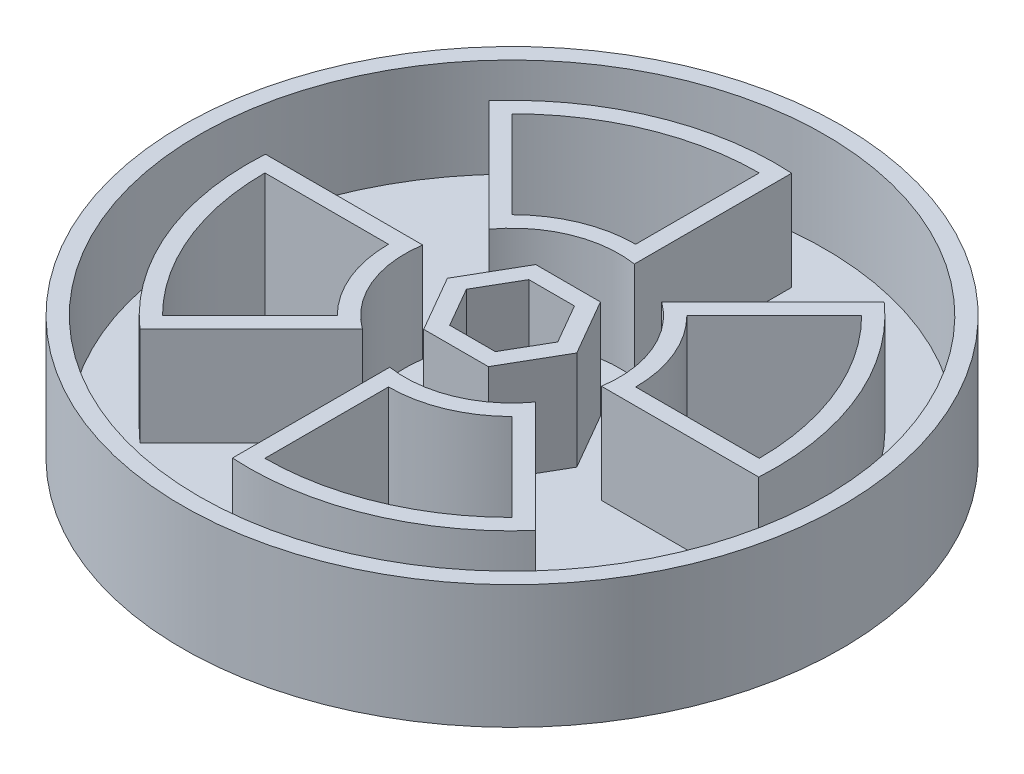
SolidWorks part; units mm, degrees
ref_plane "Front Plane" through (0, 0, 0) normal (0, 0, 1) x (1, 0, 0)
ref_plane "Top Plane" through (0, 0, 0) normal (0, 1, 0) x (1, 0, 0)
ref_plane "Right Plane" through (0, 0, 0) normal (1, 0, 0) x (0, 0, -1)
sketch "Sketch1" plane through (0, 0, 0) normal (0, 1, 0) x (1, 0, 0)
  circle A0 centre (0, 0) radius 50.8
  dimension "D1" = 101.6
extrude "Boss-Extrude1" add sketch "Sketch1" along normal blind 19.05
sketch "Sketch4" plane through (0, 19.05, 0) normal (0, 1, 0) x (1, 0, 0)
  line L0 (-3.5195, 6.096) -> (3.5195, 6.096)
  line L1 (3.5195, 6.096) -> (7.0391, 0)
  line L2 (7.0391, 0) -> (3.5195, -6.096)
  line L3 (3.5195, -6.096) -> (-3.5195, -6.096)
  line L4 (-3.5195, -6.096) -> (-7.0391, 0)
  line L5 (-7.0391, 0) -> (-3.5195, 6.096)
  point P7 (0, 6.096)
  dimension "D1" = 120
  dimension "D2" = 12.192
extrude "Cut-Extrude2" cut sketch "Sketch4" against normal blind 15.24 contours L5 L0 L1 L2 L3 L4
sketch "Sketch5" plane through (0, 3.81, 0) normal (0, 1, 0) x (1, 0, 0)
  circle A0 centre (0, 0) radius 4.064
  dimension "D1" = 8.128
extrude "Cut-Extrude3" cut sketch "Sketch5" against normal through all contours A0
sketch "Sketch6" plane through (0, 19.05, 0) normal (0, 1, 0) x (1, 0, 0)
  line L0 (0, 0) -> (0, 38.1)
  line L1 (0, 0) -> (26.9408, 26.9408)
  line L2 (0, 0) -> (38.1, 0)
  line L3 (0, 0) -> (26.9408, -26.9408)
  line L4 (0, 0) -> (0, -38.1)
  line L5 (0, 0) -> (-26.9408, -26.9408)
  line L6 (0, 0) -> (-38.1, 0)
  line L7 (0, 0) -> (-26.9408, 26.9408)
  circle A0 centre (0, 0) radius 38.1
  circle A1 centre (0, 0) radius 19.05
  point P15 (0, 0)
  dimension "D1" = 38.1
  dimension "D2" = 76.2
  dimension "D3" = 45
  dimension "D4" = 4
extrude "Cut-Extrude4" cut sketch "Sketch6" against normal through all contours A1 L0 A0 L7 | A1 L2 A0 L1 | A1 L4 A0 L3 | A1 L6 A0 L5
sketch "Sketch7" plane through (0, 19.05, 0) normal (0, 1, 0) x (1, 0, 0)
  line L27 (16.3134, -2.54) -> (40.5605, -2.54)
  line L28 (26.8846, 30.4767) -> (9.7393, 13.3314)
  line L29 (2.54, 16.3134) -> (2.54, 40.5605)
  line L30 (-30.4767, 26.8846) -> (-13.3314, 9.7393)
  line L31 (2.54, 16.3134) -> (2.54, 40.5605)
  line L32 (-30.4767, 26.8846) -> (-13.3314, 9.7393)
  line L33 (-2.54, -16.3134) -> (-2.54, -40.5605)
  line L34 (30.4767, -26.8846) -> (13.3314, -9.7393)
  line L35 (-16.3134, 2.54) -> (-40.5605, 2.54)
  line L36 (-26.8846, -30.4767) -> (-9.7393, -13.3314)
  line L64 (9.972, 0) -> (4.986, 8.636)
  line L65 (4.986, -8.636) -> (9.972, 0)
  line L66 (-4.986, -8.636) -> (4.986, -8.636)
  line L67 (-9.972, 0) -> (-4.986, -8.636)
  line L68 (-4.986, 8.636) -> (-9.972, 0)
  line L69 (4.986, 8.636) -> (-4.986, 8.636)
  line L70 (9.972, 0) -> (4.986, 8.636)
  line L71 (4.986, -8.636) -> (9.972, 0)
  line L72 (-4.986, -8.636) -> (4.986, -8.636)
  line L73 (-9.972, 0) -> (-4.986, -8.636)
  line L74 (-4.986, 8.636) -> (-9.972, 0)
  line L75 (4.986, 8.636) -> (-4.986, 8.636)
  arc A28 (40.5605, -2.54) -> (26.8846, 30.4767) centre (0, 0) ccw
  arc A29 (16.3134, -2.54) -> (9.7393, 13.3314) centre (0, 0) ccw
  arc A30 (2.54, 16.3134) -> (-13.3314, 9.7393) centre (0, 0) ccw
  arc A31 (2.54, 40.5605) -> (-30.4767, 26.8846) centre (0, 0) ccw
  arc A32 (2.54, 16.3134) -> (-13.3314, 9.7393) centre (0, 0) ccw
  arc A33 (2.54, 40.5605) -> (-30.4767, 26.8846) centre (0, 0) ccw
  arc A34 (-2.54, -40.5605) -> (30.4767, -26.8846) centre (0, 0) ccw
  arc A35 (-2.54, -16.3134) -> (13.3314, -9.7393) centre (0, 0) ccw
  arc A36 (-40.5605, 2.54) -> (-26.8846, -30.4767) centre (0, 0) ccw
  arc A37 (-16.3134, 2.54) -> (-9.7393, -13.3314) centre (0, 0) ccw
  circle A40 centre (0, 0) radius 48.26
  circle A41 centre (0, 0) radius 50.8 construction
  point P15 (0, 0)
  dimension "D4" = 2.54
  dimension "D1" = 2.54
  dimension "D3" = 2.54
  dimension "D2" = 4
extrude "gutted" cut sketch "Sketch7" against normal up to surface (15.24 mm away) contours A40 L35 A37 L36 A36 L27 A29 L28 A28 L75 L70 L71 L72 L73 L74 A33 L31 A32 L32 L33 A35 L34 A34 up to face at (0, 3.81, 4.064)
